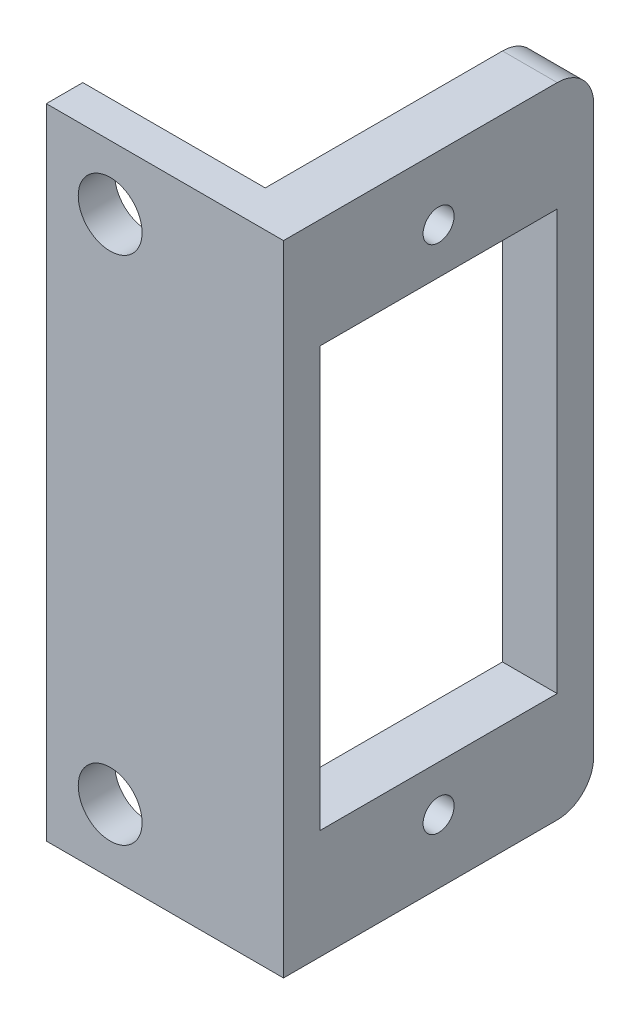
SolidWorks part; units mm, degrees
ref_plane "Plano frontal" through (0, 0, 0) normal (0, 0, 1) x (1, 0, 0)
ref_plane "Plano superior" through (0, 0, 0) normal (0, 1, 0) x (1, 0, 0)
ref_plane "Plano direito" through (0, 0, 0) normal (1, 0, 0) x (0, 0, -1)
sketch "Esboço1" plane through (0, 0, 0) normal (1, 0, 0) x (0, 0, -1)
  line L1 (-8.5, -17.5) -> (8.5, -17.5)
  line L2 (-8.5, -17.5) -> (-8.5, 17.5)
  line L3 (-8.5, 17.5) -> (8.5, 17.5)
  line L4 (8.5, -17.5) -> (8.5, 17.5)
  line L5 (-8.5, -17.5) -> (8.5, 17.5) construction
  line L6 (-8.5, 17.5) -> (8.5, -17.5) construction
  point P0 (0, 0)
  dimension "D1" = 35
  dimension "D2" = 17
extrude "Ressalto-extrusão1" add sketch "Esboço1" along normal mid plane 3
sketch "Esboço2" plane through (1.5, 0, 0) normal (1, 0, 0) x (0, 0, -1)
  line L1 (6.5, -11.5) -> (-6.5, -11.5)
  line L2 (6.5, -11.5) -> (6.5, 11.5)
  line L3 (6.5, 11.5) -> (-6.5, 11.5)
  line L4 (-6.5, -11.5) -> (-6.5, 11.5)
  line L5 (6.5, -11.5) -> (-6.5, 11.5) construction
  line L6 (6.5, 11.5) -> (-6.5, -11.5) construction
  point P0 (0, 0)
  dimension "D1" = 13
  dimension "D2" = 23
extrude "Corte-extrusão1" cut sketch "Esboço2" against normal up to next
sketch "Esboço3" plane through (-1.5, 0, 0) normal (-1, 0, 0) x (0, 0, 1)
  line L0 (-12.3301, 0) -> (12.3301, 0) construction
  circle A0 centre (0, 14) radius 0.85
  circle A1 centre (0, -14) radius 0.85
  dimension "D1" = 1.7
  dimension "D2" = 14
extrude "Corte-extrusão2" cut sketch "Esboço3" against normal up to next
fillet "Filete1" radius 2 2 edges at (0, -17.5, -8.5) (0, 17.5, -8.5)
sketch "Esboço5" plane through (0, 0, 8.5) normal (0, 0, 1) x (1, 0, 0)
  line L1 (1.5, -15.5) -> (1.5, 15.5) construction
  line L2 (1.5, 17.5) -> (-11.5, 17.5)
  line L3 (1.5, 17.5) -> (1.5, -17.5)
  line L4 (1.5, -17.5) -> (-11.5, -17.5)
  line L5 (-11.5, 17.5) -> (-11.5, -17.5)
  line L6 (1.5, 17.5) -> (-1.5, 17.5) construction
  line L7 (-1.5, -15.5) -> (-1.5, 15.5) construction
  point P9 (1.5, 0)
  dimension "D1" = 10
extrude "Ressalto-extrusão2" add sketch "Esboço5" against normal up to surface (2 mm away) up to face at (0, 0, 6.5)
sketch "Esboço6" plane through (0, 0, 6.5) normal (0, 0, 1) x (1, 0, 0)
  line L0 (-3.5, 0) -> (15.4241, 0) construction
  line L1 (-11.5, -17.5) -> (-11.5, 17.5) construction
  line L8 (1.5, 17.5) -> (-11.5, 17.5) construction
  circle A0 centre (-8, 14) radius 1.75
  circle A1 centre (-8, -14) radius 1.75
  dimension "D1" = 3.5
  dimension "D2" = 3.5
  dimension "D3" = 3.5
extrude "Corte-extrusão3" cut sketch "Esboço6" along normal up to next
